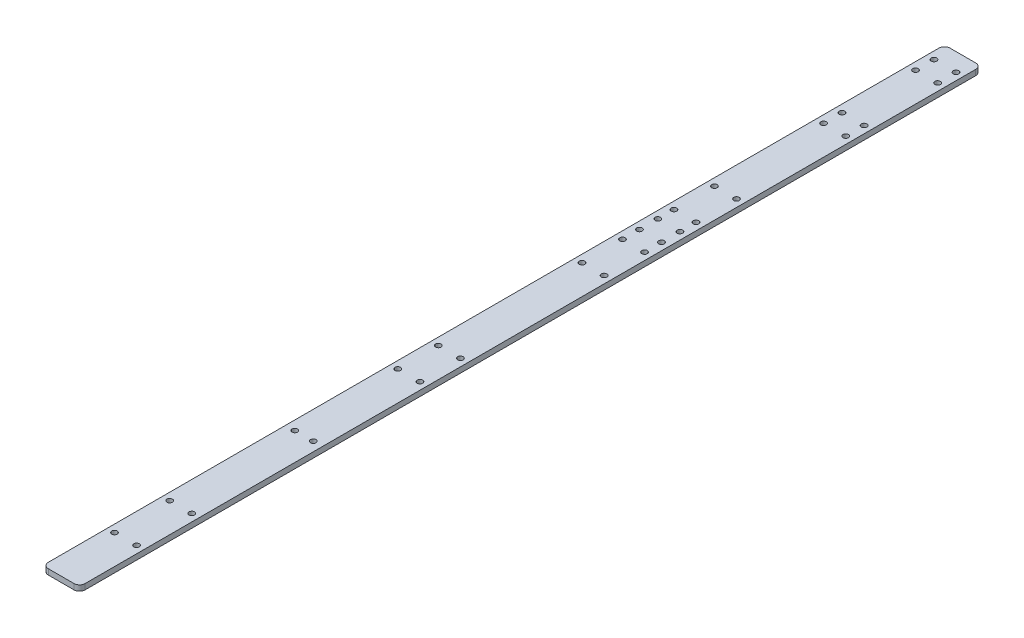
SolidWorks part; units mm, degrees
material "Thornel Mat VMA"
ref_plane "前视基准面" through (0, 0, 0) normal (0, 0, 1) x (1, 0, 0)
ref_plane "上视基准面" through (0, 0, 0) normal (0, 1, 0) x (1, 0, 0)
ref_plane "右视基准面" through (0, 0, 0) normal (1, 0, 0) x (0, 0, -1)
sketch "草图1" plane through (0, 0, 0) normal (0, 1, 0) x (1, 0, 0)
  line L0 (-9.7495, 254.1231) -> (-9.7495, -255.8769)
  line L1 (-9.7495, -255.8769) -> (10.2505, -255.8769)
  line L2 (10.2505, -255.8769) -> (10.2505, 254.1231)
  line L3 (10.2505, 254.1231) -> (-9.7495, 254.1231)
  circle A0 centre (5.2505, -103.8769) radius 1.5
  circle A1 centre (-4.7495, -103.8769) radius 1.5
  circle A2 centre (6.2134, -46.8769) radius 1.5
  circle A3 centre (-5.7866, -46.8769) radius 1.5
  circle A4 centre (6.2134, -24.8769) radius 1.5
  circle A5 centre (-5.7866, -24.8769) radius 1.5
  circle A6 centre (6.2951, 53.1231) radius 1.5
  circle A7 centre (-5.7049, 53.1231) radius 1.5
  circle A8 centre (6.2951, 75.1231) radius 1.5
  circle A9 centre (-5.7049, 75.1231) radius 1.5
  circle A10 centre (6.2634, 84.3731) radius 1.5
  circle A11 centre (-5.7366, 84.3731) radius 1.5
  circle A12 centre (6.2634, 94.3731) radius 1.5
  circle A13 centre (-5.7366, 94.3731) radius 1.5
  circle A14 centre (6.2505, 103.1231) radius 1.5
  circle A15 centre (-5.7495, 103.1231) radius 1.5
  circle A16 centre (6.2505, 125.1231) radius 1.5
  circle A17 centre (-5.7495, 125.1231) radius 1.5
  circle A18 centre (6.3451, 184.3731) radius 1.5
  circle A19 centre (-5.6549, 184.3731) radius 1.5
  circle A20 centre (6.3451, 194.3731) radius 1.5
  circle A21 centre (-5.6549, 194.3731) radius 1.5
  circle A22 centre (6.3005, 234.3731) radius 1.5
  circle A23 centre (-5.6995, 234.3731) radius 1.5
  circle A24 centre (6.3005, 244.3731) radius 1.5
  circle A25 centre (-5.6995, 244.3731) radius 1.5
extrude "凸台-拉伸1" add sketch "草图1" along normal blind 3
sketch "草图2" plane through (0, 3, 0) normal (0, 1, 0) x (1, 0, 0)
  line L0 (10.2505, -255.8769) -> (10.2505, 254.1231) construction
  line L1 (-9.7495, -255.8769) -> (10.2505, -255.8769)
  line L2 (-9.7495, -255.8769) -> (-9.7495, -235.8769)
  line L3 (-9.7495, -235.8769) -> (10.2505, -235.8769)
  line L4 (10.2505, -255.8769) -> (10.2505, -235.8769)
  dimension "D1" = 20
extrude "切除-拉伸1" cut sketch "草图2" against normal through all
fillet "圆角1" radius 3 4 edges at (-9.7495, 1.5, 235.8769) (10.2505, 1.5, 235.8769) (10.2505, 1.5, -254.1231) (-9.7495, 1.5, -254.1231)
sketch "草图3" plane through (0, 3, 0) normal (0, 1, 0) x (1, 0, 0)
  line L0 (0.2505, -235.8769) -> (0.2505, 254.1231) construction
  line L1 (7.2505, -235.8769) -> (-6.7495, -235.8769) construction
  line L2 (7.2505, 254.1231) -> (-6.7495, 254.1231) construction
  line L4 (-5.7495, -200.8769) -> (6.2505, -200.8769) construction
  line L5 (-5.7495, -200.8769) -> (-5.7495, -170.8769) construction
  line L6 (-5.7495, -170.8769) -> (6.2505, -170.8769) construction
  line L7 (6.2505, -200.8769) -> (6.2505, -170.8769) construction
  line L8 (-5.7495, -200.8769) -> (6.2505, -170.8769) construction
  line L9 (-5.7495, -170.8769) -> (6.2505, -200.8769) construction
  circle A0 centre (-5.7495, -170.8769) radius 1.5
  circle A1 centre (-5.7495, -200.8769) radius 1.5
  circle A2 centre (6.2505, -170.8769) radius 1.5
  circle A3 centre (6.2505, -200.8769) radius 1.5
  point P6 (0.2505, -185.8769)
  dimension "D4" = 3
  dimension "D5" = 3
  dimension "D1" = 12
  dimension "D2" = 30
  dimension "D3" = 50
extrude "切除-拉伸2" cut sketch "草图3" against normal through all
